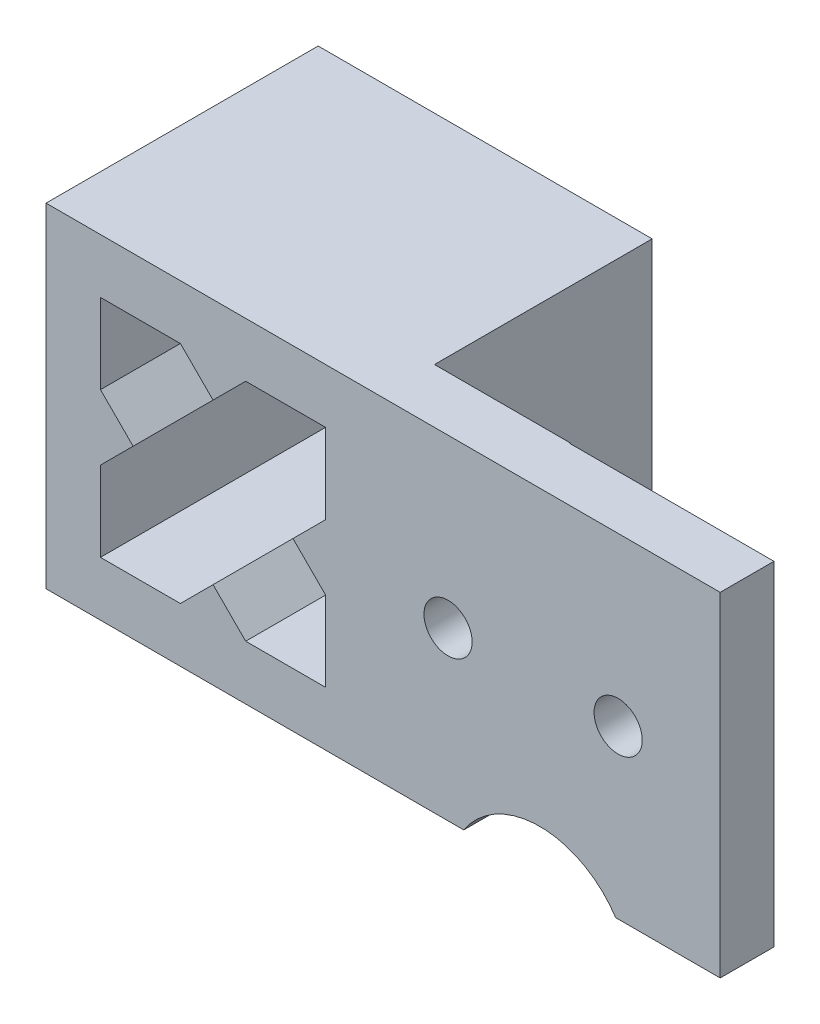
SolidWorks part; units mm, degrees
ref_plane "Front Plane" through (0, 0, 0) normal (0, 0, 1) x (1, 0, 0)
ref_plane "Top Plane" through (0, 0, 0) normal (0, 1, 0) x (1, 0, 0)
ref_plane "Right Plane" through (0, 0, 0) normal (1, 0, 0) x (0, 0, -1)
sketch "Sketch1" plane through (0, 0, 0) normal (0, 0, 1) x (1, 0, 0)
  line L5 (10, 10) -> (-10, -10) construction
  line L6 (10, -10) -> (-10, 10) construction
  line L7 (2.54, -10) -> (3.048, -10.508)
  line L8 (0, -10) -> (0, -7.46)
  line L10 (0, -7.46) -> (2.54, -10)
  line L11 (0, -7.46) -> (-2.54, -10)
  line L12 (10.508, -10.508) -> (3.048, -10.508)
  line L13 (-10.508, 10.508) -> (-10.508, 3.048)
  line L14 (10.508, 10.508) -> (3.048, 10.508)
  line L15 (10.508, 10.508) -> (10.508, 3.048)
  line L16 (-15.588, 15.588) -> (-15.588, -15.588)
  line L17 (15.588, -15.588) -> (-15.588, -15.588)
  line L18 (15.588, 15.588) -> (15.588, -15.588)
  line L19 (15.588, 15.588) -> (-15.588, 15.588)
  line L20 (-2.54, -10) -> (-3.048, -10.508)
  line L21 (-7.46, 0) -> (-10, 2.54)
  line L22 (-7.46, 0) -> (-10, -2.54)
  line L23 (-10, -2.54) -> (-10.508, -3.048)
  line L24 (-10, 2.54) -> (-10.508, 3.048)
  line L25 (0, 7.46) -> (2.54, 10)
  line L26 (0, 7.46) -> (-2.54, 10)
  line L27 (-2.54, 10) -> (-3.048, 10.508)
  line L28 (2.54, 10) -> (3.048, 10.508)
  line L29 (7.46, 0) -> (10, -2.54)
  line L30 (7.46, 0) -> (10, 2.54)
  line L31 (10, 2.54) -> (10.508, 3.048)
  line L32 (10, -2.54) -> (10.508, -3.048)
  line L33 (-3.048, 10.508) -> (-10.508, 10.508)
  line L34 (-3.048, -10.508) -> (-10.508, -10.508)
  line L35 (10.508, 10.508) -> (-10.508, 10.508) construction
  line L36 (10.508, -3.048) -> (10.508, -10.508)
  line L37 (10.508, -10.508) -> (-10.508, -10.508) construction
  line L39 (10.508, 10.508) -> (10.508, -10.508) construction
  line L40 (-10.508, -3.048) -> (-10.508, -10.508)
  line L43 (-10.508, 10.508) -> (-10.508, -10.508) construction
  point P0 (0, 0)
  point P42 (0, 0)
  dimension "D2" = 2.54
  dimension "D4" = 5.08
  dimension "D5" = 4
extrude "Boss-Extrude1" add sketch "Sketch1" along normal blind 25.4
sketch "Sketch3" plane through (15.588, 0, 0) normal (1, 0, 0) x (0, 0, -1)
  line L0 (0, 10) -> (0, -10)
  line L1 (0, -10) -> (-20, -10)
  line L3 (0, 10) -> (-20, 10)
  line L4 (-20, -10) -> (-20, 10)
  line L5 (0.381, -10.381) -> (-20.381, -10.381)
  line L6 (-20.381, -10.381) -> (-20.381, 10.381)
  line L7 (0, 15.588) -> (0, -15.588) construction
  line L8 (0.381, 10.381) -> (-20.381, 10.381)
  line L9 (0.381, 10.381) -> (0.381, -10.381)
  line L10 (0, 15.588) -> (-25.4, 15.588)
  line L11 (-25.4, 15.588) -> (-25.4, -15.588)
  line L12 (-25.4, -15.588) -> (0, -15.588)
  line L13 (0, -15.588) -> (0, -10.381)
  line L14 (0, 15.588) -> (0, 10.381)
  point P0 (0, 0)
  line M6 (0, -15.588) -> (0, 15.588)
  line M7 (0, 15.588) -> (-25.4, 15.588)
  line M8 (-25.4, 15.588) -> (-25.4, -15.588)
  line M9 (-25.4, -15.588) -> (0, -15.588)
  dimension "D1" = 20
  dimension "D2" = 20
  dimension "D3" = 0.381
extrude "Boss-Extrude2" add sketch "Sketch3" along normal blind 12.7 contours L8 L5 L6 M6 M7 M8 M9
sketch "Sketch4" plane through (0, 0, 20.381) normal (0, 0, -1) x (-1, 0, 0)
  line L0 (-15.588, 0) -> (-28.288, 0)
  line L1 (-15.588, 10.381) -> (-15.588, -10.381) construction
  line L2 (-28.288, -10.381) -> (-28.288, 10.381) construction
  circle A0 centre (-21.938, 0) radius 2.25
  dimension "D1" = 4.5
extrude "Cut-Extrude1" cut sketch "Sketch4" against normal blind 12.7 contours L0 A0 | L0 A0
sketch "Sketch5" plane through (0, -15.588, 0) normal (0, -1, 0) x (1, 0, 0)
  line L0 (28.288, 0) -> (15.588, 0)
  line L1 (28.288, 0) -> (-15.588, 0) construction
  line L2 (15.588, 0) -> (15.588, 25.4)
  line L3 (28.288, 25.4) -> (-15.588, 25.4) construction
  line L4 (15.588, 25.4) -> (28.288, 25.4)
  line L5 (28.288, 20.32) -> (28.288, 0)
  line L6 (28.288, 10.32) -> (15.588, 10.32)
  line L7 (28.288, 25.4) -> (15.588, 25.4)
  line L9 (28.288, 20.32) -> (15.588, 20.32)
  line L10 (15.588, 25.4) -> (15.588, 20.32)
  line L11 (28.288, 20.32) -> (28.288, 25.4)
  circle A0 centre (21.938, 10.32) radius 2.25
  line M10 (-15.588, 0) -> (28.288, 0)
  line M11 (28.288, 0) -> (28.288, 25.4)
  dimension "D4" = 4.5
  dimension "D1" = 12.7
  dimension "D2" = 5.08
  dimension "D3" = 10
sketch "Sketch12" plane through (0, 0, 25.4) normal (0, 0, 1) x (1, 0, 0)
  line L1 (23.4465, -17.7108) -> (24.7961, -25.067)
  line L2 (24.7961, -25.067) -> (31.8416, -27.5763)
  line L3 (31.8416, -27.5763) -> (37.5375, -22.7294)
  line L4 (37.5375, -22.7294) -> (36.1879, -15.3732)
  line L5 (36.1879, -15.3732) -> (29.1424, -12.8639)
  line L6 (29.1424, -12.8639) -> (23.4465, -17.7108)
  circle A0 centre (30.492, -20.2201) radius 6.477 construction
  dimension "D1" = 12.954
extrude "Cut-Extrude7" [suppressed] cut sketch "Sketch12" against normal through all contours L1 L2 L3 L4 L5 L6
sketch "Sketch13" [suppressed] plane through (0, 0, 25.4) normal (0, 0, 1) x (1, 0, 0)
  line L0 (25.6571, -15.588) -> (25.6571, -10.381)
  line L2 (26.9366, -14.2703) -> (23.5616, -20.3243)
  line L3 (23.5616, -20.3243) -> (27.1171, -26.2741)
  line L4 (27.1171, -26.2741) -> (34.0474, -26.1699)
  line L5 (34.0474, -26.1699) -> (37.4224, -20.1159)
  line L6 (37.4224, -20.1159) -> (33.8669, -14.1661)
  line L7 (33.8669, -14.1661) -> (26.9366, -14.2703)
  line L8 (25.6571, -10.381) -> (47.692, -10.381)
  line L9 (25.6571, -10.381) -> (25.6571, -13.7431)
  line L10 (25.6571, -13.7431) -> (47.692, -13.7431)
  line L11 (47.692, -10.381) -> (47.692, -13.7431)
  line L12 (25.6571, -10.381) -> (17.4819, -10.381)
  line L13 (25.6571, -10.381) -> (25.6571, -13.7431)
  line L14 (25.6571, -13.7431) -> (17.4819, -13.7431)
  line L15 (17.4819, -10.381) -> (17.4819, -13.7431)
  line L16 (17.4819, -10.381) -> (23.013, -10.381)
  line L17 (17.4819, -10.381) -> (17.4819, -30.2233)
  line L18 (17.4819, -30.2233) -> (23.013, -30.2233)
  line L19 (23.013, -10.381) -> (23.013, -30.2233)
  line L20 (23.013, -30.2233) -> (47.692, -30.2233)
  line L21 (23.013, -30.2233) -> (23.013, -26.6971)
  line L22 (23.013, -26.6971) -> (47.692, -26.6971)
  line L23 (47.692, -30.2233) -> (47.692, -26.6971)
  line L24 (37.971, -13.7431) -> (47.692, -13.7431)
  line L25 (37.971, -13.7431) -> (37.971, -26.6971)
  line L26 (37.971, -26.6971) -> (47.692, -26.6971)
  line L27 (47.692, -13.7431) -> (47.692, -26.6971)
  circle A0 centre (30.492, -20.2201) radius 6.0025 construction
  line M18 (28.288, -13.7773) -> (28.288, 15.588)
  line M21 (-15.588, -15.588) -> (25.6571, -15.588)
  dimension "D1" = 5.207
extrude "Boss-Extrude7" [suppressed] add sketch "Sketch13" against normal up to surface (25.4 mm away) contours L19 L22 L3 | L20 L23 L22 L4 L19 | L19 L17 L18 M21 | L19 L2 M21 | L11 L8 L7 L10 M18 | L27 L10 L25 L22 | L25 L5 L22 | L25 L10 L6
sketch "Sketch14" [suppressed] plane through (17.4819, 0, 0) normal (-1, 0, 0) x (0, 0, 1)
  line L1 (25.4, -30.2233) -> (0, -30.2233)
  line L2 (25.4, -30.2233) -> (25.4, -15.588)
  line L3 (25.4, -15.588) -> (0, -15.588)
  line L4 (0, -30.2233) -> (0, -15.588)
extrude "Boss-Extrude8" [suppressed] add sketch "Sketch14" along normal blind 5.08
sketch "Sketch18" [suppressed] plane through (0, 0, 0) normal (0, 0, -1) x (-1, 0, 0)
  line L0 (-12.4019, -15.588) -> (-12.4019, -30.2233) construction
  line L1 (-47.692, -30.2233) -> (-12.4019, -30.2233)
  line L2 (-47.692, -30.2233) -> (-47.692, -10.381)
  line L3 (-47.692, -10.381) -> (-12.4019, -10.381)
  line L4 (-12.4019, -30.2233) -> (-12.4019, -10.381)
  line L5 (-47.692, -10.381) -> (-15.588, -10.381) construction
  dimension "D1" = 0
  dimension "D2" = 0
extrude "Cut-Extrude9" [suppressed] cut sketch "Sketch18" against normal up to surface (0.381 mm away)
sketch "Sketch19" [suppressed] plane through (47.692, 0, 0) normal (1, 0, 0) x (0, 0, -1)
  line L1 (-0.381, -10.381) -> (-20.381, -10.381)
  line L2 (-0.381, -10.381) -> (-0.381, -16.731)
  line L3 (-0.381, -16.731) -> (-20.381, -16.731)
  line L4 (-20.381, -10.381) -> (-20.381, -16.731)
  dimension "D1" = 6.35
  dimension "D2" = 20
extrude "Boss-Extrude9" [suppressed] add sketch "Sketch19" along normal blind 12.7
sketch "Sketch20" [suppressed] plane through (0, -16.731, 0) normal (0, -1, 0) x (1, 0, 0)
  line L0 (60.392, 20.381) -> (47.692, 0.381)
  point P4 (54.042, 10.381)
hole_wizard "M4 Clearance Hole1" [suppressed] positions "Sketch21" profile "Sketch22" hole size "M4" standard "ANSI Metric"
sketch "Sketch21" [suppressed] plane through (0, -16.731, 0) normal (0, -1, 0) x (-1, 0, 0)
  point P0 (-54.042, -10.381)
sketch "Sketch22" plane through (54.042, -16.731, 10.381) normal (1, 0, 0) x (0, 0, -1)
  line L0 (0, 0) -> (0, 32.319)
  line L1 (0, 32.319) -> (2.25, 32.319)
  line L2 (2.25, 32.319) -> (2.25, 0)
  line L5 (2.25, 0) -> (0, 0)
  line L11 (0, -6.35) -> (0, 107.95) construction
  dimension "Thru Hole Dia." = 4.5
  dimension "Thru Hole Depth" = 32.319
sketch "Sketch23" [suppressed] plane through (0, 0, 20.381) normal (0, 0, 1) x (1, 0, 0)
  line L1 (60.392, -16.731) -> (47.692, -16.731)
  line L2 (60.392, -16.731) -> (60.392, -10.381)
  line L3 (60.392, -10.381) -> (47.692, -10.381)
  line L4 (47.692, -16.731) -> (47.692, -10.381)
extrude "Boss-Extrude10" [suppressed] add sketch "Sketch23" along normal up to surface (5.019 mm away)
sketch "Sketch25" [suppressed] plane through (0, 0, 25.4) normal (0, 0, 1) x (1, 0, 0)
  line L1 (23.6793, -20.4676) -> (27.3, -26.2438)
  line L2 (27.3, -26.2438) -> (34.1127, -25.9963)
  line L3 (34.1127, -25.9963) -> (37.3047, -19.9726)
  line L4 (37.3047, -19.9726) -> (33.684, -14.1964)
  line L5 (33.684, -14.1964) -> (26.8713, -14.4439)
  line L6 (26.8713, -14.4439) -> (23.6793, -20.4676)
  circle A0 centre (30.492, -20.2201) radius 3.81
  circle A1 centre (30.492, -20.2201) radius 5.9038 construction
  dimension "D1" = 7.62
sketch "Sketch26" [suppressed] plane through (0, 0, 25.4) normal (0, 0, 1) x (1, 0, 0)
  line L0 (60.392, -16.731) -> (47.692, -30.2233)
  line L1 (47.692, -30.2233) -> (47.692, -16.731)
  line L2 (47.692, -16.731) -> (60.392, -16.731)
extrude "Boss-Extrude13" [suppressed] add sketch "Sketch26" against normal blind 6.35
sketch "Sketch27" [suppressed] plane through (0, 0, 25.4) normal (0, 0, 1) x (1, 0, 0)
  line L0 (-15.588, -15.588) -> (12.4019, -30.2233)
  line L1 (12.4019, -30.2233) -> (12.4019, -15.588)
  line L2 (12.4019, -15.588) -> (-15.588, -15.588)
extrude "Boss-Extrude14" [suppressed] add sketch "Sketch27" against normal blind 6.35
ref_plane "Plane1" through (0, 0, 0) normal (0, -1, 0) x (-1, 0, 0)
sketch "Sketch28" [suppressed] plane through (0, 0, 0.381) normal (0, 0, -1) x (-1, 0, 0)
  line L1 (-47.692, -30.2233) -> (-12.4019, -30.2233)
  line L2 (-47.692, -30.2233) -> (-47.692, -10.381)
  line L3 (-47.692, -10.381) -> (-12.4019, -10.381)
  line L4 (-12.4019, -30.2233) -> (-12.4019, -10.381)
  line L5 (-32.594, -24.7373) -> (-53.1064, -40.1197)
  line L6 (-53.1064, -40.1197) -> (-50.0411, -65.5752)
  line L7 (-50.0411, -65.5752) -> (-26.4634, -75.6483)
  line L8 (-26.4634, -75.6483) -> (-5.9509, -60.2659)
  line L9 (-5.9509, -60.2659) -> (-9.0162, -34.8104)
  line L10 (-9.0162, -34.8104) -> (-32.594, -24.7373)
  circle A0 centre (-29.5287, -50.1928) radius 22.2043 construction
sketch "Sketch29" plane through (0, 0, 25.4) normal (0, 0, 1) x (1, 0, 0)
  circle A0 centre (30.492, -20.2201) radius 8.4687
  dimension "D1" = 16.9375
extrude "Cut-Extrude10" cut sketch "Sketch29" against normal through all
extrude "Cut-Extrude11" cut sketch "Sketch5" against normal through all contours A0 L6 L5 L9 L2 | A0 L6 L2 M10 M11 | L6 A0 | L6 A0
sketch "Sketch30" plane through (0, 0, 25.4) normal (0, 0, 1) x (1, 0, 0)
  line L0 (28.288, 15.588) -> (47.338, 15.588)
  line L1 (47.338, 15.588) -> (47.338, -15.588)
  line L2 (47.338, -15.588) -> (37.5817, -15.588)
  line L3 (23.4023, -15.588) -> (-15.588, -15.588) construction
  line L4 (28.288, 15.588) -> (28.288, -12.0432) construction
  circle A0 centre (30.492, -20.2201) radius 8.4687
  circle A1 centre (37.813, 0) radius 2.25
  circle A2 centre (21.938, 0) radius 2.25
  circle A3 centre (21.938, 0) radius 2.25 construction
  line M7 (28.288, -12.0432) -> (28.288, 15.588)
  dimension "D3" = 0
  dimension "D1" = 0
  dimension "D2" = 19.05
extrude "Boss-Extrude15" add sketch "Sketch30" against normal up to surface (5.019 mm away) contours A0 L2 L1 L0 A1 M7 up to face at (19.688, 0, 20.381)
